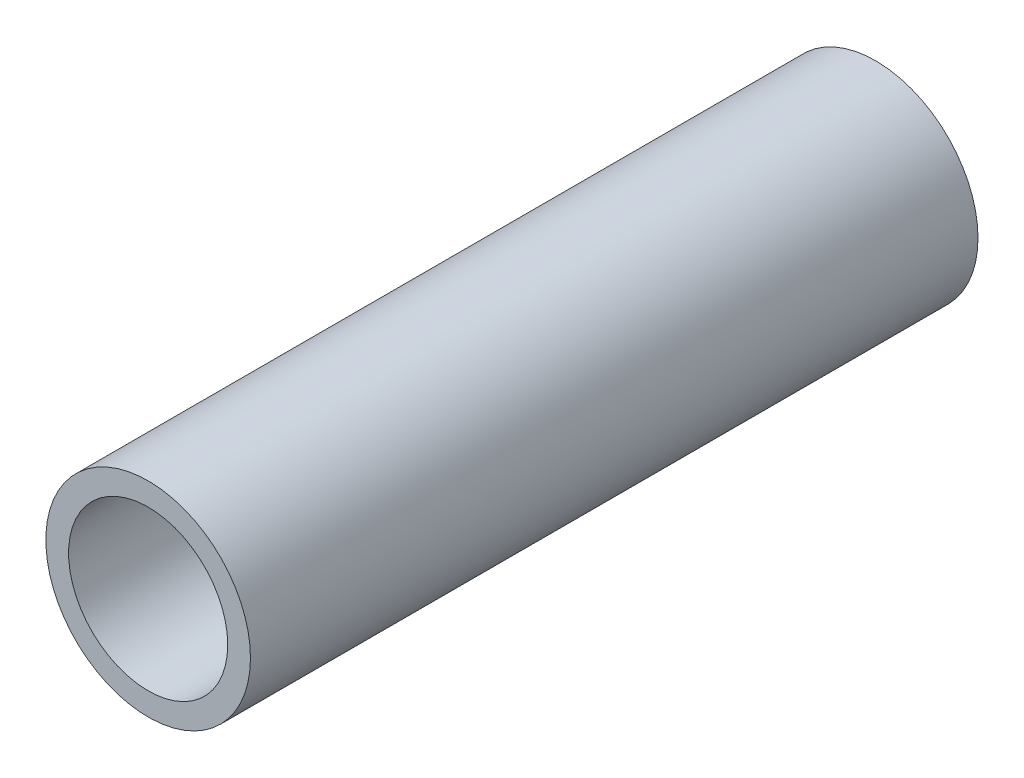
SolidWorks part; units mm, degrees
ref_plane "XZ (Face)" through (0, 0, 0) normal (0, 0, 1) x (1, 0, 0)
ref_plane "XY (Dessus)" through (0, 0, 0) normal (0, 1, 0) x (1, 0, 0)
ref_plane "YZ (Droite)" through (0, 0, 0) normal (1, 0, 0) x (0, 0, -1)
sketch "Esquisse1" plane through (0, 0, 0) normal (0, 0, 1) x (1, 0, 0)
  circle A1 centre (0, 9) radius 2.25
  circle A2 centre (0, 9) radius 1.75
  dimension "D2" = 4.5
  dimension "D1" = 0.5
extrude "Base-Extrusion" add sketch "Esquisse1" along normal mid plane 16
